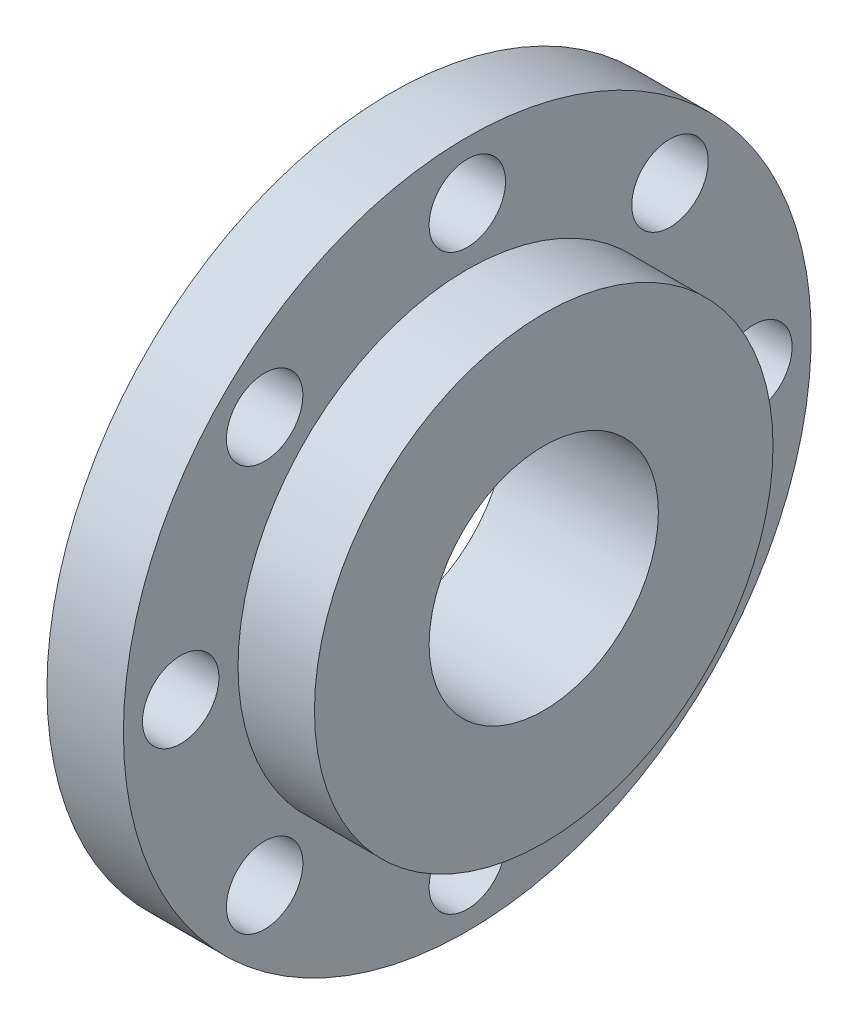
SolidWorks part; units mm, degrees
ref_plane "Front Plane" through (0, 0, 0) normal (0, 0, 1) x (1, 0, 0)
ref_plane "Top Plane" through (0, 0, 0) normal (0, 1, 0) x (1, 0, 0)
ref_plane "Right Plane" through (0, 0, 0) normal (1, 0, 0) x (0, 0, -1)
sketch "Sketch2" plane through (0, 0, 0) normal (0, 0, 1) x (1, 0, 0)
  line L0 (0, 0) -> (38.8393, 0) construction
  line L1 (0, 15) -> (20, 15)
  line L2 (20, 15) -> (20, 30)
  line L3 (10, 30) -> (10, 45)
  line L4 (10, 45) -> (0, 45)
  line L5 (0, 45) -> (0, 15)
  line L6 (20, 30) -> (10, 30)
  dimension "D1" = 90
  dimension "D2" = 10
  dimension "D3" = 30
  dimension "D4" = 10
  dimension "D5" = 60
revolve "Revolve1" add sketch "Sketch2" angle 360 about L0
sketch "Sketch3" plane through (0, 0, 0) normal (-1, 0, 0) x (0, 0, 1)
  circle A0 centre (0, 0) radius 37.5 construction
  circle A1 centre (0, 37.5) radius 5
  circle A2 centre (26.5165, 26.5165) radius 5
  circle A3 centre (37.5, 0) radius 5
  circle A4 centre (26.5165, -26.5165) radius 5
  circle A5 centre (0, -37.5) radius 5
  circle A6 centre (-26.5165, -26.5165) radius 5
  circle A7 centre (-37.5, 0) radius 5
  circle A8 centre (-26.5165, 26.5165) radius 5
  point P21 (0, 0)
  dimension "D1" = 75
  dimension "D2" = 10
  dimension "D3" = 8
extrude "Cut-Extrude1" cut sketch "Sketch3" against normal through all
